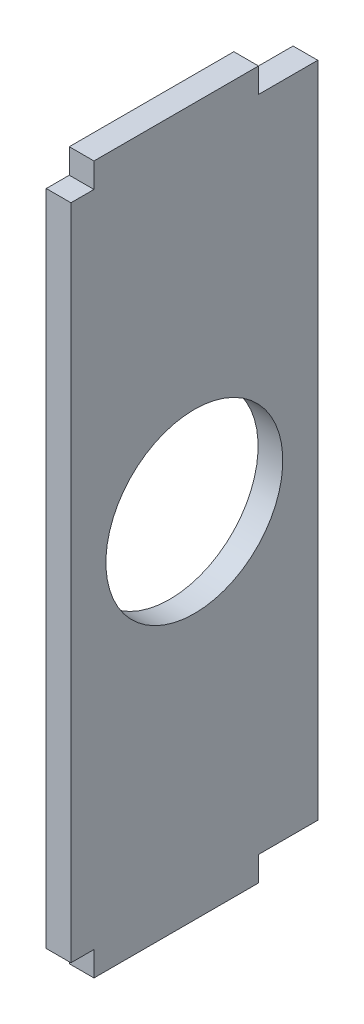
SolidWorks part; units mm, degrees
ref_plane "Plan de face" through (0, 0, 0) normal (0, 0, 1) x (1, 0, 0)
ref_plane "Plan de dessus" through (0, 0, 0) normal (0, 1, 0) x (1, 0, 0)
ref_plane "Plan de droite" through (0, 0, 0) normal (1, 0, 0) x (0, 0, -1)
ref_plane "Plan1" through (-3, 0, 0) normal (-1, 0, 0) x (0, -1, 0)
sketch "Esquisse1" plane through (-3, 0, 0) normal (-1, 0, 0) x (0, -1, 0)
  line L0 (40, 15) -> (-40, 15)
  line L1 (-40, 15) -> (-40, 12.2)
  line L2 (-40, 12.2) -> (-43, 12.2)
  line L3 (-43, 12.2) -> (-43, -7.8)
  line L4 (-43, -7.8) -> (-40, -7.8)
  line L5 (-40, -7.8) -> (-40, -15)
  line L6 (-40, -15) -> (40, -15)
  line L7 (40, -15) -> (40, -7.8)
  line L8 (40, -7.8) -> (43, -7.8)
  line L9 (43, -7.8) -> (43, 12.2)
  line L10 (43, 12.2) -> (40, 12.2)
  line L11 (40, 12.2) -> (40, 15)
  circle A2 centre (0, 0) radius 10.75
  dimension "D1" = 21.5
extrude "Boss.-Extru.1" add sketch "Esquisse1" against normal blind 3
